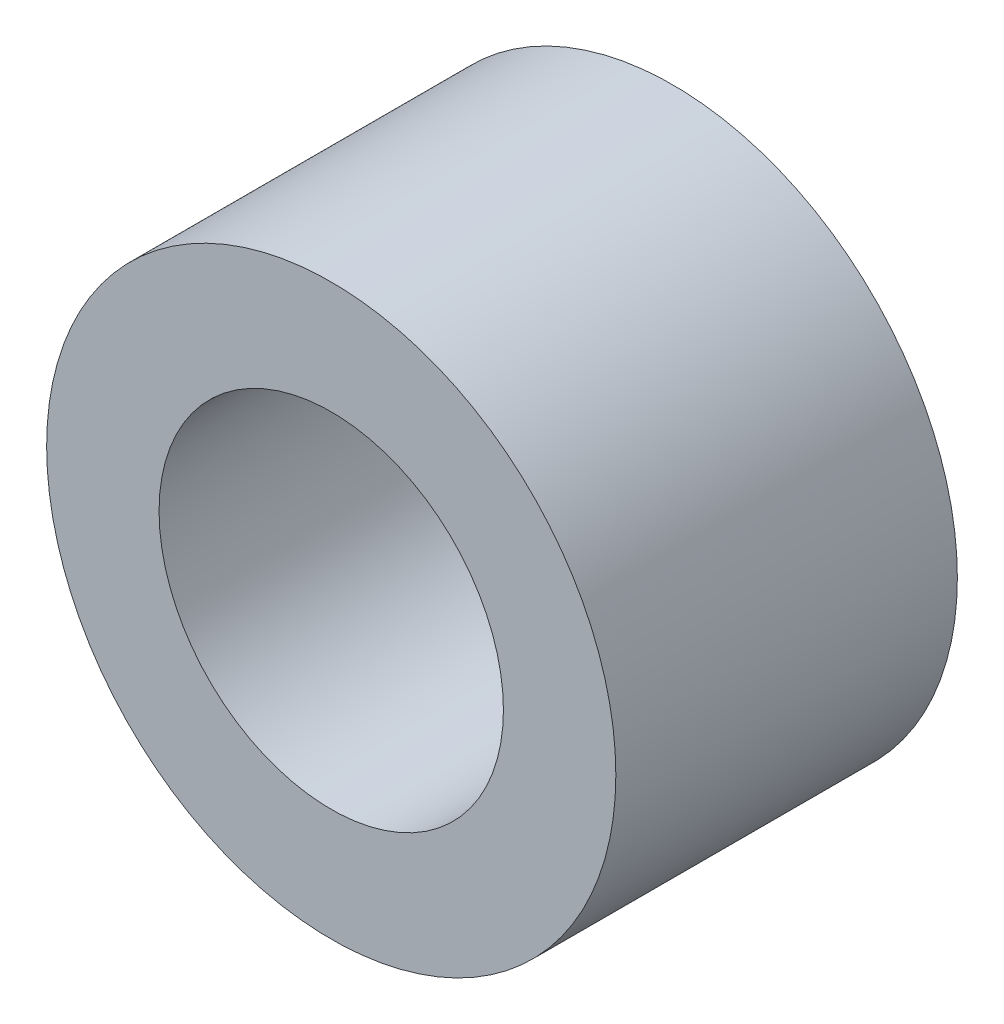
SolidWorks part; units mm, degrees
material "Custom Plastic"
ref_plane "X-Y Datum" through (0, 0, 0) normal (0, 0, 1) x (1, 0, 0)
ref_plane "X-Z Datum" through (0, 0, 0) normal (0, 1, 0) x (1, 0, 0)
ref_plane "Y-Z Datum" through (0, 0, 0) normal (1, 0, 0) x (0, 0, -1)
sketch "Sketch1" plane through (0, 0, 0) normal (0, 0, 1) x (1, 0, 0)
  circle A0 centre (0, 0) radius 5
  dimension "D1" = 10
extrude "Boss-Extrude1" add sketch "Sketch1" along normal blind 6
sketch "Sketch2" plane through (0, 0, 6) normal (0, 0, 1) x (1, 0, 0)
  circle A0 centre (0, 0) radius 3.025
  dimension "D1" = 6.05
extrude "Cut-Extrude1" cut sketch "Sketch2" against normal blind 5.5
